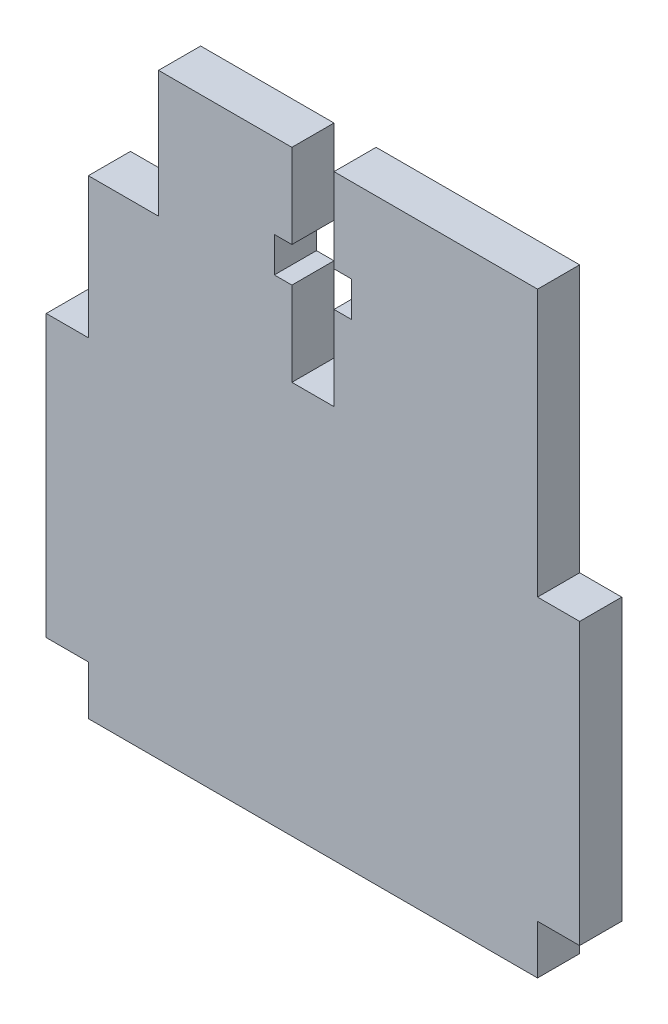
SolidWorks part; units mm, degrees
ref_plane "Спереди" through (0, 0, 0) normal (0, 0, 1) x (1, 0, 0)
ref_plane "Сверху" through (0, 0, 0) normal (0, 1, 0) x (1, 0, 0)
ref_plane "Справа" through (0, 0, 0) normal (1, 0, 0) x (0, 0, -1)
sketch "Эскиз1" plane through (0, 0, 0) normal (0, 0, 1) x (1, 0, 0)
  line L1 (0, 0) -> (32, 0)
  line L2 (0, 0) -> (0, 42.5)
  line L3 (0, 42.5) -> (32, 42.5)
  line L4 (32, 0) -> (32, 42.5)
  dimension "D1" = 32
  dimension "D2" = 42.5
extrude "Бобышка-Вытянуть1" add sketch "Эскиз1" along normal blind 3
sketch "Эскиз2" plane through (32, 0, 0) normal (1, 0, 0) x (0, 0, -1)
  line L0 (-3, 0) -> (-3, 42.5) construction
  line L1 (-3, 3.5) -> (0, 3.5)
  line L2 (-3, 3.5) -> (-3, 23.5)
  line L3 (-3, 23.5) -> (0, 23.5)
  line L4 (0, 3.5) -> (0, 23.5)
  line L5 (0, 0) -> (0, 42.5) construction
  dimension "D1" = 20
  dimension "D2" = 3.5
extrude "Бобышка-Вытянуть2" add sketch "Эскиз2" along normal blind 3 and the other way blind 35
sketch "Эскиз3" plane through (0, 0, 3) normal (0, 0, 1) x (1, 0, 0)
  line L0 (14.5, 42.5) -> (14.5, 36.5)
  line L1 (14.5, 36.5) -> (13.25, 36.5)
  line L2 (13.25, 36.5) -> (13.25, 34)
  line L3 (13.25, 34) -> (14.5, 34)
  line L4 (14.5, 34) -> (14.5, 28)
  line L5 (14.5, 28) -> (17.5, 28)
  line L6 (17.5, 28) -> (17.5, 34)
  line L7 (17.5, 34) -> (18.75, 34)
  line L8 (18.75, 34) -> (18.75, 36.5)
  line L9 (18.75, 36.5) -> (17.5, 36.5)
  line L10 (17.5, 36.5) -> (17.5, 42.5)
  line L11 (17.5, 42.5) -> (14.5, 42.5)
  line L12 (32, 42.5) -> (0, 42.5) construction
  point P14 (16, 42.5)
  point P15 (16, 42.5)
  dimension "D1" = 6
  dimension "D2" = 2.5
  dimension "D3" = 3
  dimension "D4" = 5.5
extrude "Вырез-Вытянуть1" cut sketch "Эскиз3" against normal blind 3
sketch "Эскиз4" plane through (0, 0, 3) normal (0, 0, 1) x (1, 0, 0)
  line L1 (0, 42.5) -> (5, 42.5)
  line L2 (0, 42.5) -> (0, 33.5)
  line L3 (0, 33.5) -> (5, 33.5)
  line L4 (5, 42.5) -> (5, 33.5)
  dimension "D1" = 9
  dimension "D2" = 5
extrude "Вырез-Вытянуть2" cut sketch "Эскиз4" against normal blind 3
